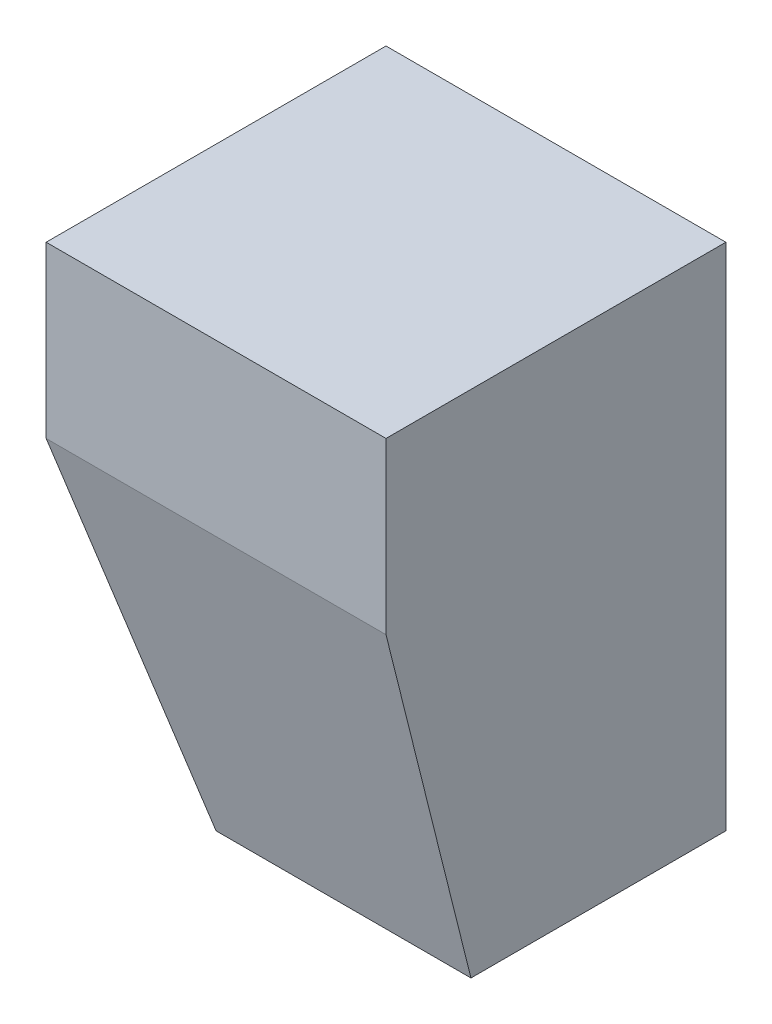
SolidWorks part; units mm, degrees
ref_plane "Front Plane" through (0, 0, 0) normal (0, 0, 1) x (1, 0, 0)
ref_plane "Top Plane" through (0, 0, 0) normal (0, 1, 0) x (1, 0, 0)
ref_plane "Right Plane" through (0, 0, 0) normal (1, 0, 0) x (0, 0, -1)
sketch "Sketch1" plane through (0, 0, 0) normal (0, 1, 0) x (1, 0, 0)
  line L1 (25.4, 25.4) -> (-25.4, 25.4)
  line L2 (25.4, 25.4) -> (25.4, -25.4)
  line L3 (25.4, -25.4) -> (-25.4, -25.4)
  line L4 (-25.4, 25.4) -> (-25.4, -25.4)
  line L5 (25.4, 25.4) -> (-25.4, -25.4) construction
  line L6 (25.4, -25.4) -> (-25.4, 25.4) construction
  point P0 (0, 0)
  dimension "D1" = 50.8
  dimension "D2" = 50.8
extrude "Boss-Extrude1" add sketch "Sketch1" along normal blind 76.2
chamfer "Chamfer1" distance 12.7 distance2 50.8 1 edges at (0, 0, 25.4)
chamfer "Chamfer2" distance 12.7 distance2 50.8 1 edges at (-25.4, 0, -6.35)
